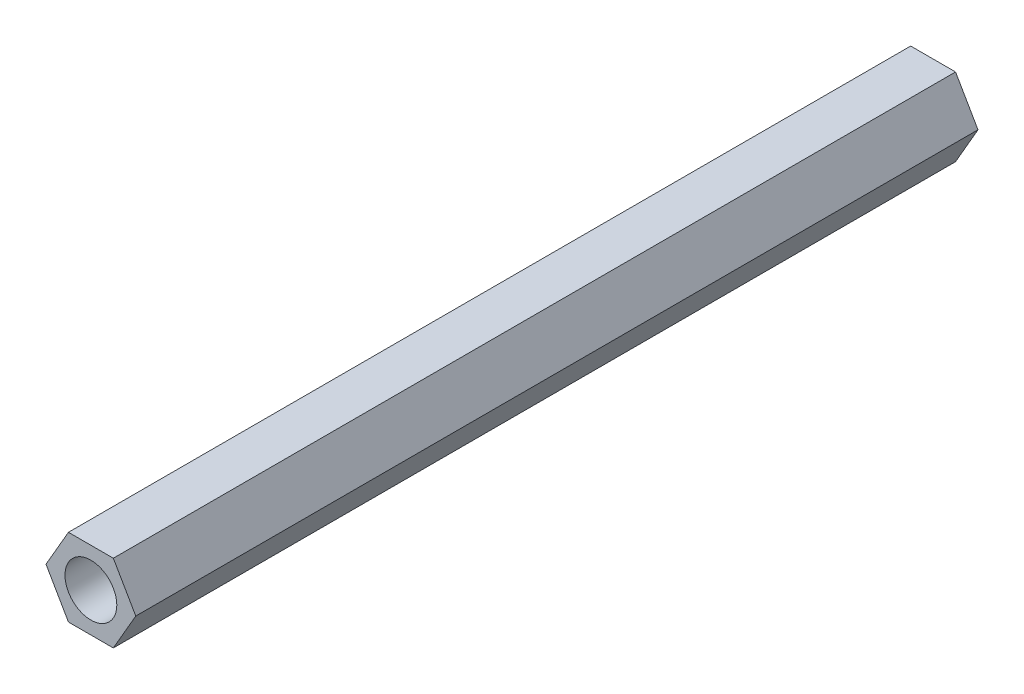
SolidWorks part; units mm, degrees
ref_plane "Plan de face" through (0, 0, 0) normal (0, 0, 1) x (1, 0, 0)
ref_plane "Plan de dessus" through (0, 0, 0) normal (0, 1, 0) x (1, 0, 0)
ref_plane "Plan de droite" through (0, 0, 0) normal (1, 0, 0) x (0, 0, -1)
sketch "Esquisse1" plane through (0, 0, 0) normal (0, 0, 1) x (1, 0, 0)
  line L1 (-3.4641, 0) -> (-1.7321, -3)
  line L2 (-1.7321, -3) -> (1.7321, -3)
  line L3 (1.7321, -3) -> (3.4641, 0)
  line L4 (3.4641, 0) -> (1.7321, 3)
  line L5 (1.7321, 3) -> (-1.7321, 3)
  line L6 (-1.7321, 3) -> (-3.4641, 0)
  circle A0 centre (0, 0) radius 2
  circle A1 centre (0, 0) radius 3 construction
  dimension "D1" = 4
  dimension "D2" = 6
extrude "Boss.-Extru.1" add sketch "Esquisse1" along normal blind 65
